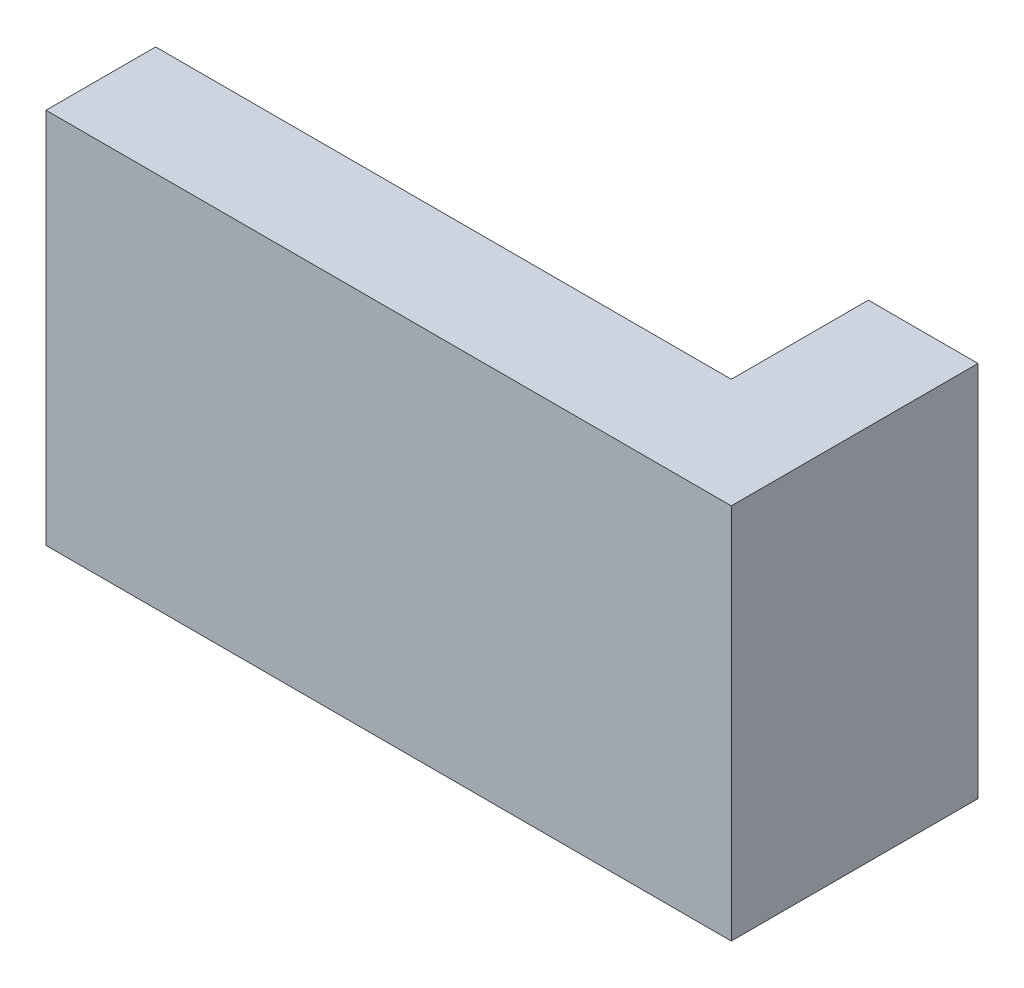
SolidWorks part; units mm, degrees
ref_plane "Front Plane" through (0, 0, 0) normal (0, 0, 1) x (1, 0, 0)
ref_plane "Top Plane" through (0, 0, 0) normal (0, 1, 0) x (1, 0, 0)
ref_plane "Right Plane" through (0, 0, 0) normal (1, 0, 0) x (0, 0, -1)
sketch "Sketch2" plane through (0, 0, 0) normal (0, 0, 1) x (1, 0, 0)
  line L1 (-19.2126, 9.4094) -> (-9.2126, 9.4094)
  line L2 (-19.2126, 9.4094) -> (-19.2126, 3.9094)
  line L3 (-19.2126, 3.9094) -> (-9.2126, 3.9094)
  line L4 (-9.2126, 9.4094) -> (-9.2126, 3.9094)
  dimension "D1" = 10
  dimension "D2" = 5.5
extrude "Boss-Extrude1" add sketch "Sketch2" along normal blind 1.6 contours L1 L4 L3 L2
sketch "Sketch3" plane through (0, 0, 0) normal (0, 0, -1) x (-1, 0, 0)
  line L0 (19.2126, 3.9094) -> (9.2126, 3.9094) construction
  line L2 (9.2126, 9.4094) -> (10.8126, 9.4094)
  line L3 (9.2126, 9.4094) -> (9.2126, 3.9094)
  line L4 (9.2126, 3.9094) -> (10.8126, 3.9094)
  line L5 (10.8126, 9.4094) -> (10.8126, 3.9094)
  dimension "D1" = 1.6
extrude "Boss-Extrude2" add sketch "Sketch3" along normal blind 2
